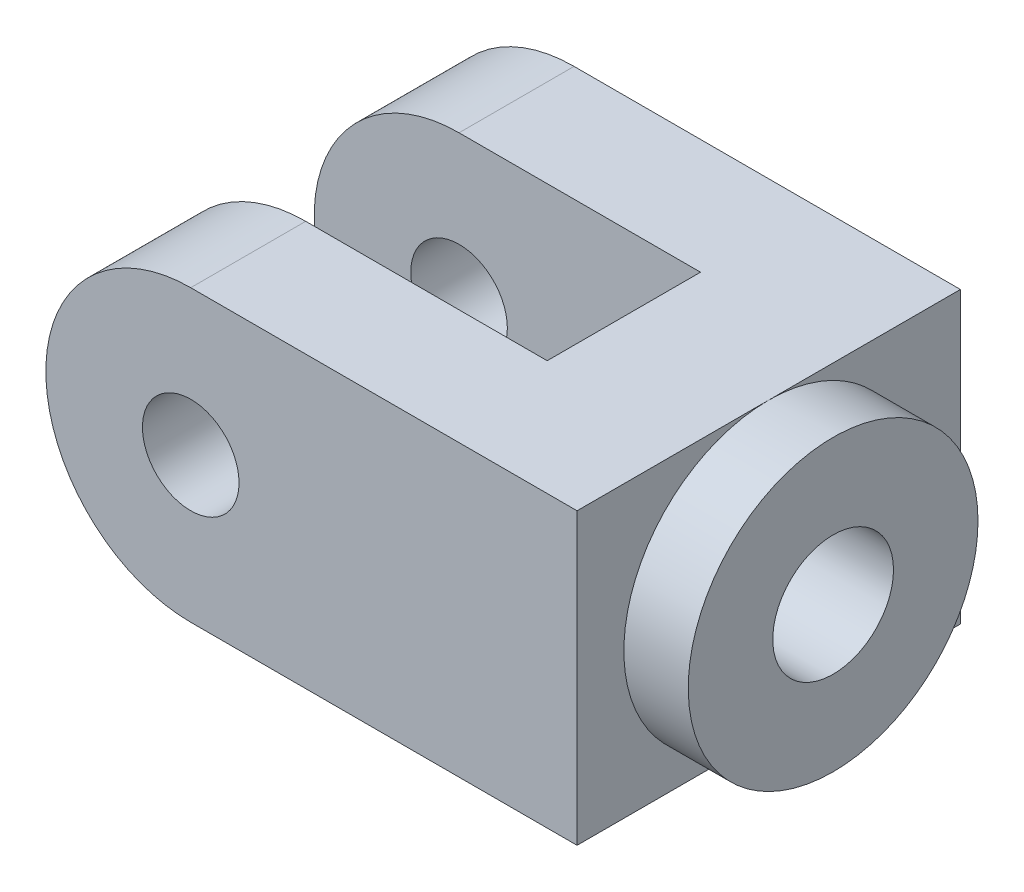
SolidWorks part; units mm, degrees
ref_plane "Front Plane" through (0, 0, 0) normal (0, 0, 1) x (1, 0, 0)
ref_plane "Top Plane" through (0, 0, 0) normal (0, 1, 0) x (1, 0, 0)
ref_plane "Right Plane" through (0, 0, 0) normal (1, 0, 0) x (0, 0, -1)
sketch "Sketch1" plane through (0, 0, 0) normal (0, 0, 1) x (1, 0, 0)
  line L1 (66, -36) -> (-66, -36)
  line L2 (66, -36) -> (66, 36)
  line L3 (66, 36) -> (-66, 36)
  line L4 (-66, -36) -> (-66, 36)
  line L5 (66, -36) -> (-66, 36) construction
  line L6 (66, 36) -> (-66, -36) construction
  point P0 (0, 0)
  dimension "D1" = 132
  dimension "D2" = 72
extrude "Boss-Extrude1" add sketch "Sketch1" along normal mid plane 95.25
sketch "Sketch2" plane through (0, 0, 47.625) normal (0, 0, 1) x (1, 0, 0)
  line L0 (66, 36) -> (-66, 36) construction
  line L1 (-66, -36) -> (66, -36) construction
  line L2 (-66, 36) -> (-66, -36) construction
  arc A0 (-30, 36) -> (-30, -36) centre (-30, 0) ccw
  dimension "D1" = 36
extrude "Cut-Extrude1" cut sketch "Sketch2" against normal through all and the other way through all flip side to cut
sketch "Sketch3" plane through (0, 36, 0) normal (0, 1, 0) x (1, 0, 0)
  line L0 (-66, 47.625) -> (-66, -47.625) construction
  line L1 (30, 19.05) -> (-66, 19.05)
  line L2 (30, 19.05) -> (30, -19.05)
  line L3 (30, -19.05) -> (-66, -19.05)
  line L4 (-66, 19.05) -> (-66, -19.05)
  line L5 (-66, -47.625) -> (-30, -47.625) construction
  line L6 (-30, -47.625) -> (-30, 47.625) construction
  dimension "D1" = 38.1
  dimension "D2" = 28.575
  dimension "D3" = 60
extrude "Cut-Extrude2" cut sketch "Sketch3" against normal through all
sketch "Sketch4" plane through (66, 0, 0) normal (1, 0, 0) x (0, 0, -1)
  circle A0 centre (0, 0) radius 15
  dimension "D1" = 30
extrude "Cut-Extrude3" cut sketch "Sketch4" against normal through all
sketch "Sketch5" plane through (66, 0, 0) normal (1, 0, 0) x (0, 0, -1)
  circle A0 centre (0, 0) radius 36
  circle A1 centre (0, 0) radius 15 construction
  circle A2 centre (0, 0) radius 15
  dimension "D1" = 72
extrude "Boss-Extrude2" add sketch "Sketch5" along normal blind 16
sketch "Sketch6" plane through (0, 0, 47.625) normal (0, 0, 1) x (1, 0, 0)
  circle A0 centre (-30, 0) radius 12
  arc A1 (-30, 36) -> (-30, -36) centre (-30, 0) ccw construction
  dimension "D1" = 24
extrude "Cut-Extrude4" cut sketch "Sketch6" against normal through all
